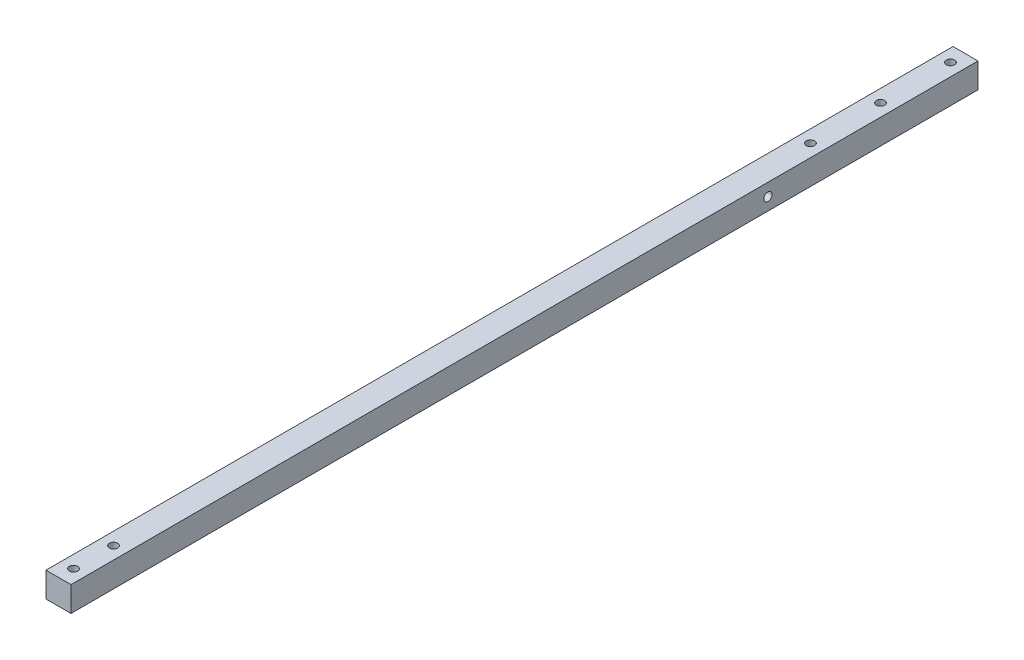
SolidWorks part; units mm, degrees
ref_plane "Plan de face" through (0, 0, 0) normal (0, 0, 1) x (1, 0, 0)
ref_plane "Plan de dessus" through (0, 0, 0) normal (0, 1, 0) x (1, 0, 0)
ref_plane "Plan de droite" through (0, 0, 0) normal (1, 0, 0) x (0, 0, -1)
sketch "Esquisse1" plane through (0, 0, 0) normal (0, 0, 1) x (1, 0, 0)
  line L1 (-3.75, -3.75) -> (3.75, -3.75)
  line L2 (-3.75, -3.75) -> (-3.75, 3.75)
  line L3 (-3.75, 3.75) -> (3.75, 3.75)
  line L4 (3.75, -3.75) -> (3.75, 3.75)
  line L5 (-3.75, -3.75) -> (3.75, 3.75) construction
  line L6 (-3.75, 3.75) -> (3.75, -3.75) construction
  point P0 (0, 0)
  dimension "D1" = 7.5
extrude "Boss.-Extru.1" add sketch "Esquisse1" along normal blind 272
sketch "Esquisse2" plane through (0, 3.75, 0) normal (0, 1, 0) x (1, 0, 0)
  line L0 (0, 0) -> (0, -46.5) construction
  line L1 (3.75, 0) -> (-3.75, 0) construction
  line L2 (0, -272) -> (0, -255.5) construction
  line L3 (3.75, -272) -> (-3.75, -272) construction
  circle A0 centre (0, -4.5) radius 1.25
  circle A1 centre (0, -25.5) radius 1.25
  circle A2 centre (0, -46.5) radius 1.25
  circle A3 centre (0, -255.5) radius 1.25
  circle A4 centre (0, -267.5) radius 1.25
  dimension "D1" = 2.5
  dimension "D2" = 21
  dimension "D3" = 21
  dimension "D4" = 4.5
  dimension "D5" = 4.5
  dimension "D6" = 12
extrude "Enlèv. mat.-Extru.1" cut sketch "Esquisse2" against normal through all
sketch "Esquisse3" plane through (3.75, 0, 0) normal (1, 0, 0) x (0, 0, -1)
  circle A0 centre (-63, 0) radius 1.25
  dimension "D1" = 2.5
  dimension "D2" = 63
extrude "Enlèv. mat.-Extru.2" cut sketch "Esquisse3" against normal through all
